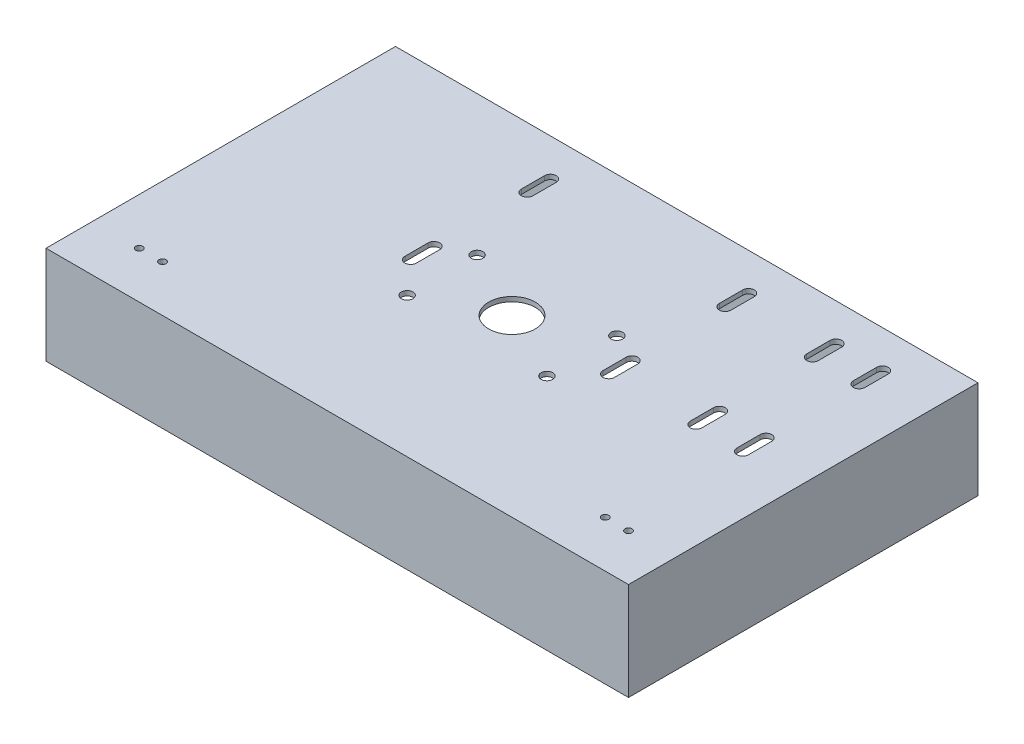
SolidWorks part; units mm, degrees
ref_plane "Front Plane" through (0, 0, 0) normal (0, 0, 1) x (1, 0, 0)
ref_plane "Top Plane" through (0, 0, 0) normal (0, 1, 0) x (1, 0, 0)
ref_plane "Right Plane" through (0, 0, 0) normal (1, 0, 0) x (0, 0, -1)
sketch "Sketch1" plane through (0, 0, 0) normal (0, 1, 0) x (1, 0, 0)
  line L1 (125, 75) -> (-125, 75)
  line L2 (125, 75) -> (125, -75)
  line L3 (125, -75) -> (-125, -75)
  line L4 (-125, 75) -> (-125, -75)
  line L5 (125, 75) -> (-125, -75) construction
  line L6 (125, -75) -> (-125, 75) construction
  point P0 (0, 0)
extrude "Boss-Extrude1" add sketch "Sketch1" along normal blind 2
sketch "Sketch2" plane through (0, 2, 0) normal (0, 1, 0) x (1, 0, 0)
  circle A0 centre (0, 0) radius 10
extrude "Cut-Extrude1" cut sketch "Sketch2" against normal blind 2
sketch "Sketch3" plane through (0, 0, 0) normal (0, -1, 0) x (1, 0, 0)
  line L0 (0, -54) -> (0, -63.9406) construction
  line L2 (40, -54) -> (0, -54) construction
  line L3 (-40, -9) -> (-40, 1)
  line L4 (-45, 1) -> (-45, -9)
  line L5 (-40, -49) -> (-40, -59)
  line L6 (-45, -49) -> (-45, -59)
  line L12 (40, -9) -> (40, 1)
  line L13 (45, 1) -> (45, -9)
  line L14 (40, -49) -> (40, -59)
  line L15 (45, -49) -> (45, -59)
  arc A0 (-40, 1) -> (-45, 1) centre (-42.5, 1) ccw
  arc A1 (-45, -9) -> (-40, -9) centre (-42.5, -9) ccw
  arc A2 (-40, -49) -> (-45, -49) centre (-42.5, -49) ccw
  arc A3 (-45, -59) -> (-40, -59) centre (-42.5, -59) ccw
  arc A4 (45, -9) -> (40, -9) centre (42.5, -9) cw
  arc A5 (40, 1) -> (45, 1) centre (42.5, 1) cw
  arc A6 (45, -59) -> (40, -59) centre (42.5, -59) cw
  arc A7 (40, -49) -> (45, -49) centre (42.5, -49) cw
sketch "Sketch7" plane through (0, 2, 0) normal (0, 1, 0) x (1, 0, 0)
  line L0 (125, 75) -> (100, 75) construction
  line L1 (125, 75) -> (-125, 75) construction
  line L2 (100, 75) -> (100, 59) construction
  line L3 (102.5, 59) -> (102.5, 49)
  line L4 (97.5, 59) -> (97.5, 49)
  line L5 (97.5, 59) -> (90, 59) construction
  line L6 (90, 59) -> (90, 64.3087) construction
  line L7 (77.5, 59) -> (77.5, 49)
  line L8 (82.5, 59) -> (82.5, 49)
  line L9 (100, 46.5) -> (100, 29) construction
  line L10 (100, 29) -> (108.4108, 29) construction
  line L11 (82.5, -1) -> (82.5, 9)
  line L12 (77.5, -1) -> (77.5, 9)
  line L13 (97.5, -1) -> (97.5, 9)
  line L14 (102.5, -1) -> (102.5, 9)
  arc A0 (102.5, 59) -> (97.5, 59) centre (100, 59) ccw
  arc A1 (97.5, 49) -> (102.5, 49) centre (100, 49) ccw
  arc A2 (82.5, 49) -> (77.5, 49) centre (80, 49) cw
  arc A3 (77.5, 59) -> (82.5, 59) centre (80, 59) cw
  arc A4 (77.5, -1) -> (82.5, -1) centre (80, -1) ccw
  arc A5 (82.5, 9) -> (77.5, 9) centre (80, 9) ccw
  arc A6 (97.5, 9) -> (102.5, 9) centre (100, 9) cw
  arc A7 (102.5, -1) -> (97.5, -1) centre (100, -1) cw
extrude "Cut-Extrude46" cut sketch "Sketch7" against normal blind 10
extrude "Cut-Extrude59" cut sketch "Sketch3" against normal blind 10
sketch "Sketch9" plane through (0, 2, 0) normal (0, 1, 0) x (1, 0, 0)
  line L0 (0, 0) -> (-30, 0) construction
  line L1 (-30, 0) -> (-30, 15) construction
  line L3 (-30, 0) -> (-30, -15) construction
  line L4 (0, 0) -> (0, 15) construction
  circle A0 centre (-30, 15) radius 2.5
  circle A1 centre (-30, -15) radius 2.5
  circle A2 centre (30, -15) radius 2.5
  circle A3 centre (30, 15) radius 2.5
extrude "Cut-Extrude60" cut sketch "Sketch9" against normal blind 10
sketch "Sketch19" plane through (0, 2, 0) normal (0, 1, 0) x (1, 0, 0)
  line L0 (125, -75) -> (125, 75) construction
  line L1 (-125, -75) -> (125, -75) construction
  line L2 (0, -75) -> (0, -101.6029) construction
  circle A0 centre (105, -55) radius 1.5
  circle A1 centre (95, -55) radius 1.5
  circle A2 centre (-95, -55) radius 1.5
  circle A3 centre (-105, -55) radius 1.5
  dimension "D1" = 20
  dimension "D2" = 20
  dimension "D3" = 30
  dimension "D4" = 20
extrude "Cut-Extrude63" cut sketch "Sketch19" against normal blind 10
sketch "Sketch20" plane through (0, 0, 0) normal (0, -1, 0) x (1, 0, 0)
  line L1 (-125, 75) -> (125, 75)
  line L2 (-125, 75) -> (-125, -75)
  line L3 (-125, -75) -> (125, -75)
  line L4 (125, 75) -> (125, -75)
  line L5 (120, 70) -> (-120, 70)
  line L6 (120, 70) -> (120, -70)
  line L7 (120, -70) -> (-120, -70)
  line L8 (-120, 70) -> (-120, -70)
  line L9 (120, 70) -> (-120, -70) construction
  line L10 (120, -70) -> (-120, 70) construction
  point P6 (0, 0)
  dimension "D1" = 5
  dimension "D2" = 5
extrude "Boss-Extrude5" add sketch "Sketch20" along normal blind 40
